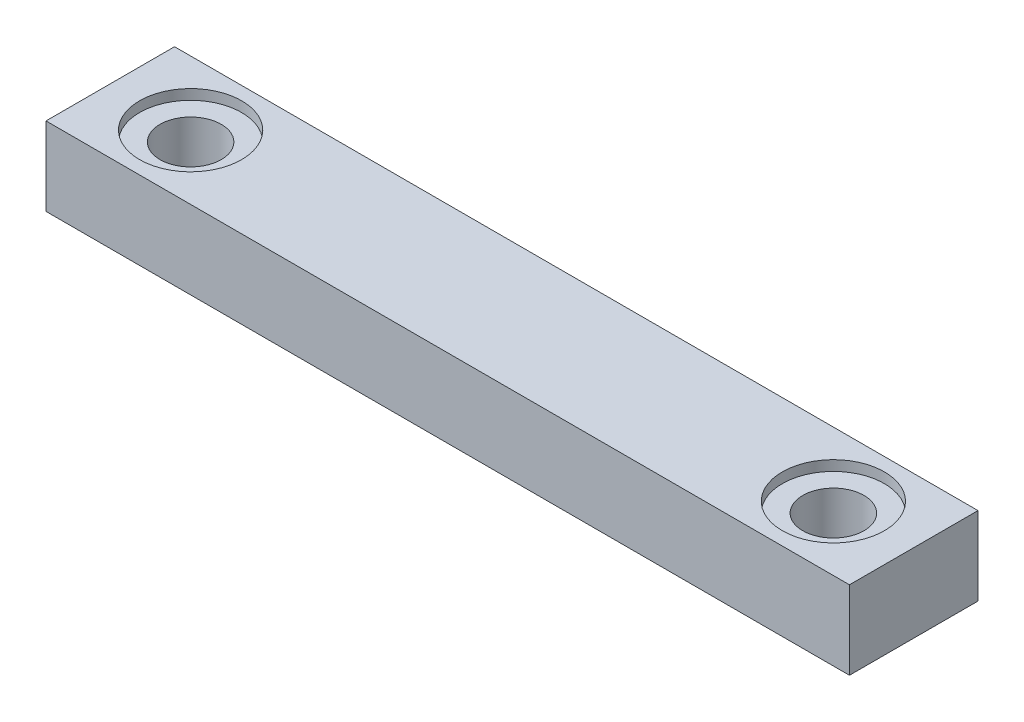
SolidWorks part; units mm, degrees
material "6061 Alloy"
ref_plane "Front Plane" through (0, 0, 0) normal (0, 0, 1) x (1, 0, 0)
ref_plane "Top Plane" through (0, 0, 0) normal (0, 1, 0) x (1, 0, 0)
ref_plane "Right Plane" through (0, 0, 0) normal (1, 0, 0) x (0, 0, -1)
sketch "Sketch1" plane through (0, 0, 0) normal (0, 1, 0) x (1, 0, 0)
  line L0 (125, 0) -> (-125, 0)
  line L1 (-125, 20) -> (125, 20)
  line L2 (-125, 20) -> (-125, -20)
  line L3 (-125, -20) -> (125, -20)
  line L4 (125, 20) -> (125, -20)
  line L5 (-125, 20) -> (125, -20) construction
  line L6 (-125, -20) -> (125, 20) construction
  line L7 (-100, -20) -> (100, -20)
  line L8 (-100, -20) -> (-100, 20)
  line L9 (-100, 20) -> (100, 20)
  line L10 (100, -20) -> (100, 20)
  line L11 (-100, -20) -> (100, 20) construction
  line L12 (-100, 20) -> (100, -20) construction
  circle A0 centre (-100, 0) radius 15.875
  circle A1 centre (100, 0) radius 15.875
  circle A2 centre (-100, 0) radius 9.525
  circle A3 centre (100, 0) radius 9.525
  point P0 (0, 0)
  point P6 (0, 0)
  point P14 (0, 0)
  dimension "D4" = 31.75
  dimension "D5" = 31.75
  dimension "D6" = 19.05
  dimension "D7" = 19.05
  dimension "D1" = 40
  dimension "D2" = 250
  dimension "D3" = 200
extrude "Boss-Extrude1" add sketch "Sketch1" along normal blind 24.3927 contours A0 L8 L1 L2 L0 | L8 A0 L0 | L0 A0 L8 | L8 A0 L0 | L0 A0 L8 | A0 L0 L2 L3 L8 | A1 L10 L1 L8 A0 L0 | A1 L0 A0 L8 L3 L10 | L0 A1 L10 | L10 A1 L0 | L0 A1 L10 | L10 A1 L0 | A1 L10 L3 L4 L0 | A1 L0 L4 L1 L10
sketch "Sketch3" plane through (0, 24.3927, 0) normal (0, 1, 0) x (1, 0, 0)
  circle A0 centre (-100, 0) radius 15.875
  circle A1 centre (100, 0) radius 15.875
extrude "Cut-Extrude1" cut sketch "Sketch3" against normal blind 3.175
equation "\"w\"= .04"
equation "\"dist\"= .2"
equation "\"E\"= 68.9 * ( 10 ^ 9 )"
equation "\"del\"= 0.0001"
equation "\"F\"= 2000"
equation "\"I\"= ( \"F\" * ( \"dist\" ^ 3 ) ) / ( 48 * \"E\" * \"del\" )"
equation "\"h\"= ( ( 12 * \"I\" ) / \"w\" ) ^ ( 1 / 3 )"
equation "\"b\"= \"w\" / 0.0254"
equation "\"dis\"= \"dist\" / 0.0254"
equation "\"L\"= .25 / 0.0254"
equation "\"t\"= \"h\" / 0.0254"
equation "\"d1\"= 1 + ( 1 / 4 )"
equation "\"D2@Sketch1\"=\"L\""
equation "\"D1@Sketch1\"=\"b\""
equation "\"D3@Sketch1\"=\"dis\""
equation "\"D4@Sketch1\"=\"d1\""
equation "\"D5@Sketch1\"=\"d1\""
equation "\"D1@Boss-Extrude1\"=\"t\""
equation "\"t2\"= 1 / 8"
equation "\"D1@Cut-Extrude1\"=\"t2\""
equation "\"d2\"= 3 / 4"
equation "\"D7@Sketch1\"=\"d2\""
equation "\"D6@Sketch1\"=\"d2\""
